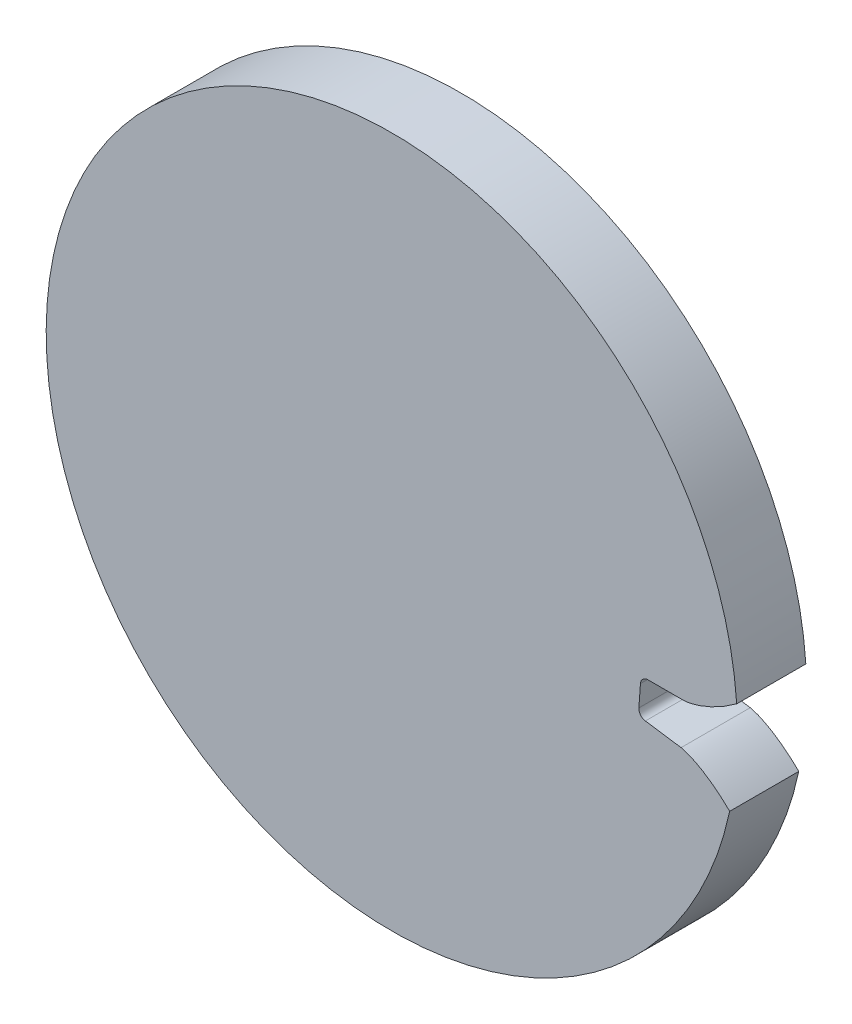
SolidWorks part; units mm, degrees
ref_plane "Front Plane" through (0, 0, 0) normal (0, 0, 1) x (1, 0, 0)
ref_plane "Top Plane" through (0, 0, 0) normal (0, 1, 0) x (1, 0, 0)
ref_plane "Right Plane" through (0, 0, 0) normal (1, 0, 0) x (0, 0, -1)
sketch "Sketch2" plane through (0, 0, 0) normal (0, 0, 1) x (1, 0, 0)
  circle A0 centre (0, 0) radius 50
  dimension "D1" = 100
extrude "Boss-Extrude1" add sketch "Sketch2" along normal blind 10
sketch "Sketch3" plane through (0, 0, 0) normal (0, 0, 1) x (1, 0, 0)
  circle A0 centre (0, 0) radius 45 construction
  circle A1 centre (0, 0) radius 42.2862 construction
  circle A2 centre (0, 0) radius 36.0362
  point P5 (0, 0)
  dimension "D1" = 72.0723
  dimension "D2" = 84.5723
  dimension "D3" = 90
sketch "Sketch4" plane through (0, 0, 10) normal (0, 0, 1) x (1, 0, 0)
  line L0 (14.7905, 0) -> (15.2451, 0)
  line L1 (0, 0) -> (49.8692, -3.6149) construction
  line L2 (31.3041, -4.5624) -> (32.0183, -4.6664)
  line L3 (42.2862, 0) -> (36.0362, 0)
  line L4 (41.8441, -6.0985) -> (35.6594, -5.1971)
  line L5 (35.6594, -5.1971) -> (36.0362, 0)
  circle A0 centre (0, 0) radius 36.0362 construction
  circle A1 centre (0, 0) radius 50 construction
  spline S0 degree 4 poles (42.2862, 0) (42.3006, 0.0002) (42.3412, 0.0014) (42.4177, 0.0063) (42.5425, 0.0178) (42.7012, 0.0379) (42.9058, 0.0698) (43.1462, 0.1152) (43.4093, 0.1733) (43.6945, 0.2452) (43.9778, 0.3247) (44.2592, 0.4112) (44.5385, 0.5038) (44.8752, 0.6236) (45.2768, 0.7777) (45.7429, 0.9732) (46.2671, 1.2127) (46.7963, 1.4759) (47.3128, 1.7505) (47.8292, 2.0456) (48.3251, 2.3437) (48.8341, 2.6713) (49.301, 2.9827) (49.8169, 3.3513) (50.2312, 3.6544) (50.7697, 4.0749) (51.0853, 4.3293) (51.4517, 4.6342) (51.6129, 4.7732) (51.7122, 4.8588) knots 0 0 0 0 0 0.005377 0.015084 0.028532 0.04661 0.064855 0.092111 0.119476 0.146842 0.174209 0.201575 0.228941 0.256307 0.307035 0.361767 0.4165 0.471232 0.525964 0.580697 0.635429 0.690161 0.744894 0.799626 0.854358 0.909091 0.954545 1 1 1 1 1 construction
  spline S1 degree 4 poles (42.2862, 0) (42.3006, 0.0002) (42.3412, 0.0014) (42.4177, 0.0063) (42.5425, 0.0178) (42.7012, 0.0379) (42.9058, 0.0698) (43.1462, 0.1152) (43.4093, 0.1733) (43.6945, 0.2452) (43.9778, 0.3247) (44.2592, 0.4112) (44.5385, 0.5038) (44.8752, 0.6236) (45.2768, 0.7777) (45.7429, 0.9732) (46.2671, 1.2127) (46.7963, 1.4759) (47.3128, 1.7505) (47.8292, 2.0456) (48.3251, 2.3437) (48.8341, 2.6713) (49.301, 2.9827) (49.8169, 3.3513) (50.2312, 3.6544) (50.6529, 3.9837) (50.8572, 4.1463) (50.9613, 4.2305) knots 0 0 0 0 0 0.005377 0.015084 0.028532 0.04661 0.064855 0.092111 0.119476 0.146842 0.174209 0.201575 0.228941 0.256307 0.307035 0.361767 0.4165 0.471232 0.525964 0.580697 0.635429 0.690161 0.744894 0.799626 0.854358 0.909091 0.909091 0.909091 0.909091 0.909091
  spline S2 degree 4 poles (41.8441, -6.0985) (41.8584, -6.1008) (41.8983, -6.1078) (41.9734, -6.1237) (42.0952, -6.1531) (42.2494, -6.1958) (42.4472, -6.2569) (42.6785, -6.3365) (42.9305, -6.4319) (43.2023, -6.5443) (43.4712, -6.6638) (43.7372, -6.79) (44.0002, -6.9219) (44.3161, -7.0889) (44.6913, -7.2994) (45.1243, -7.56) (45.6085, -7.8727) (46.0942, -8.2095) (46.5657, -8.5556) (47.0342, -8.9221) (47.4819, -9.2886) (47.9384, -9.6862) (48.3554, -10.0617) (48.8128, -10.5008) (49.179, -10.8605) (49.6512, -11.3542) (49.9268, -11.6516) (50.2455, -12.006) (50.3849, -12.1669) (50.4709, -12.2659) knots 0 0 0 0 0 0.005377 0.015084 0.028532 0.04661 0.064855 0.092111 0.119476 0.146842 0.174209 0.201575 0.228941 0.256307 0.307035 0.361767 0.4165 0.471232 0.525964 0.580697 0.635429 0.690161 0.744894 0.799626 0.854358 0.909091 0.954545 1 1 1 1 1 construction
  spline S3 degree 4 poles (41.8441, -6.0985) (41.8584, -6.1008) (41.8983, -6.1078) (41.9734, -6.1237) (42.0952, -6.1531) (42.2494, -6.1958) (42.4472, -6.2569) (42.6785, -6.3365) (42.9305, -6.4319) (43.2023, -6.5443) (43.4712, -6.6638) (43.7372, -6.79) (44.0002, -6.9219) (44.3161, -7.0889) (44.6913, -7.2994) (45.1243, -7.56) (45.6085, -7.8727) (46.0942, -8.2095) (46.5657, -8.5556) (47.0342, -8.9221) (47.4819, -9.2886) (47.9384, -9.6862) (48.3554, -10.0617) (48.8128, -10.5008) (49.179, -10.8605) (49.5489, -11.2472) (49.7276, -11.4376) (49.8184, -11.5358) knots 0 0 0 0 0 0.005377 0.015084 0.028532 0.04661 0.064855 0.092111 0.119476 0.146842 0.174209 0.201575 0.228941 0.256307 0.307035 0.361767 0.4165 0.471232 0.525964 0.580697 0.635429 0.690161 0.744894 0.799626 0.854358 0.909091 0.909091 0.909091 0.909091 0.909091
  dimension "D1" = 4.146
  dimension "D2" = 4.146
extrude "Cut-Extrude1" cut sketch "Sketch4" against normal through all and the other way through all contours S1 L3 L5 L4 S3
fillet "Fillet2" radius 1.1 2 edges at (36.0362, 0, 5) (35.6594, -5.1971, 5)
equation "\"p\"= 2'pitch"
equation "\"N\"= 18'number of teeth"
equation "\"phi\"= 20deg'pressure angle"
equation "\"a\"= 1 / \"p\"'addendum"
equation "\"b\" = 1.25 / \"p\"'dedendum"
equation "\"c\"= \"b\" - \"a\"'clearance"
equation "\"dp\"= \"N\" / \"p\"'pitch circle diameter"
equation "\"db\"= \"dp\" * cos ( \"phi\" )'base circle diameter"
equation "\"D1@Sketch2\"= \"dp\" + 2 * \"a\"'addendum circle diameter"
equation "\"D3@Sketch3\"= \"dp\" 'pitch circle dia"
equation "\"D2@Sketch3\"= \"db\" 'base circle dia"
equation "\"D1@Sketch3\"= \"db\" - 2 * \"b\" 'didenum circle dia"
equation "\"alpha\" = sqr ( \"dp\" ^ 2 - \"db\" ^ 2 ) / \"db\" * 180 / pi - \"phi\""
equation "\"D1@Sketch4\"= 360 / ( 4 * \"N\" ) - \"alpha\""
equation "\"D2@Sketch4\"= 360 / ( 4 * \"N\" ) - \"alpha\""
